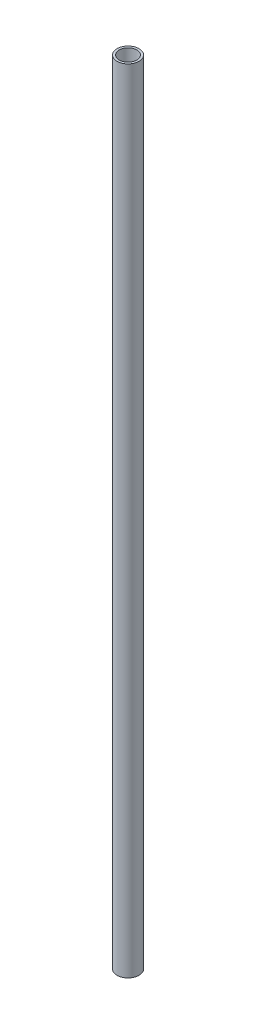
SolidWorks part; units mm, degrees
ref_plane "Plano frontal" through (0, 0, 0) normal (0, 0, 1) x (1, 0, 0)
ref_plane "Plano superior" through (0, 0, 0) normal (0, 1, 0) x (1, 0, 0)
ref_plane "Plano direito" through (0, 0, 0) normal (1, 0, 0) x (0, 0, -1)
sketch "Esboço1" plane through (0, 0, 0) normal (0, 1, 0) x (1, 0, 0)
  circle A0 centre (33.0852, 40.359) radius 2.5
  circle A1 centre (33.0852, 40.359) radius 2
extrude "Ressalto-extrusão1" add sketch "Esboço1" along normal blind 180
